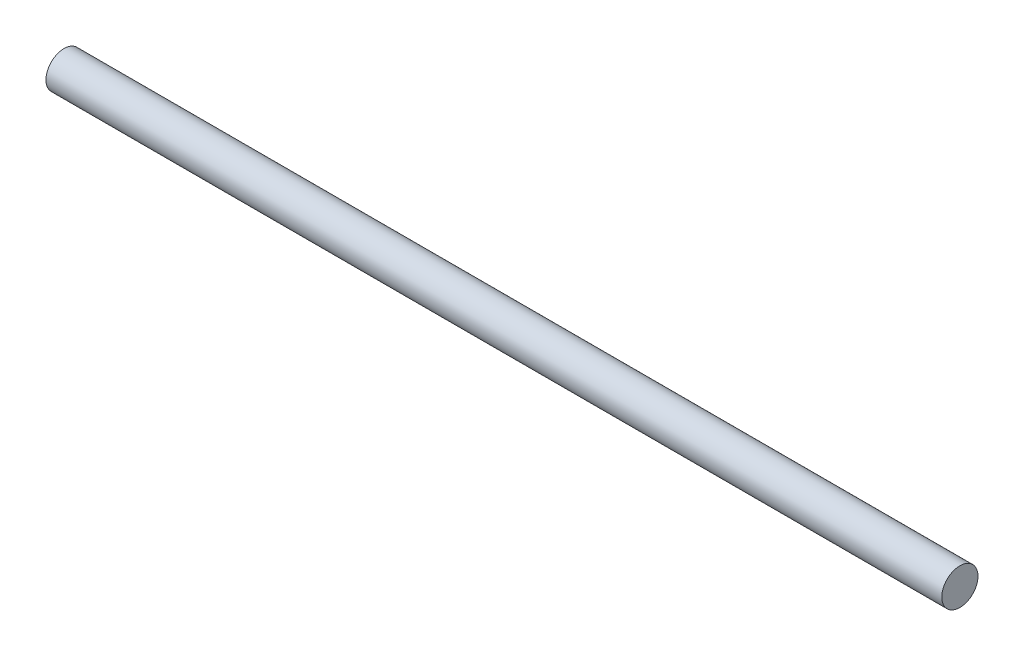
SolidWorks part; units mm, degrees
material "Copper"
ref_plane "Front Plane" through (0, 0, 0) normal (0, 0, 1) x (1, 0, 0)
ref_plane "Top Plane" through (0, 0, 0) normal (0, 1, 0) x (1, 0, 0)
ref_plane "Right Plane" through (0, 0, 0) normal (1, 0, 0) x (0, 0, -1)
sketch "Sketch1" plane through (0, 0, 0) normal (1, 0, 0) x (0, 0, -1)
  circle A0 centre (0, 0) radius 0.2921
  dimension "D1" = 0.5842
extrude "Boss-Extrude1" add sketch "Sketch1" along normal blind 14.45
